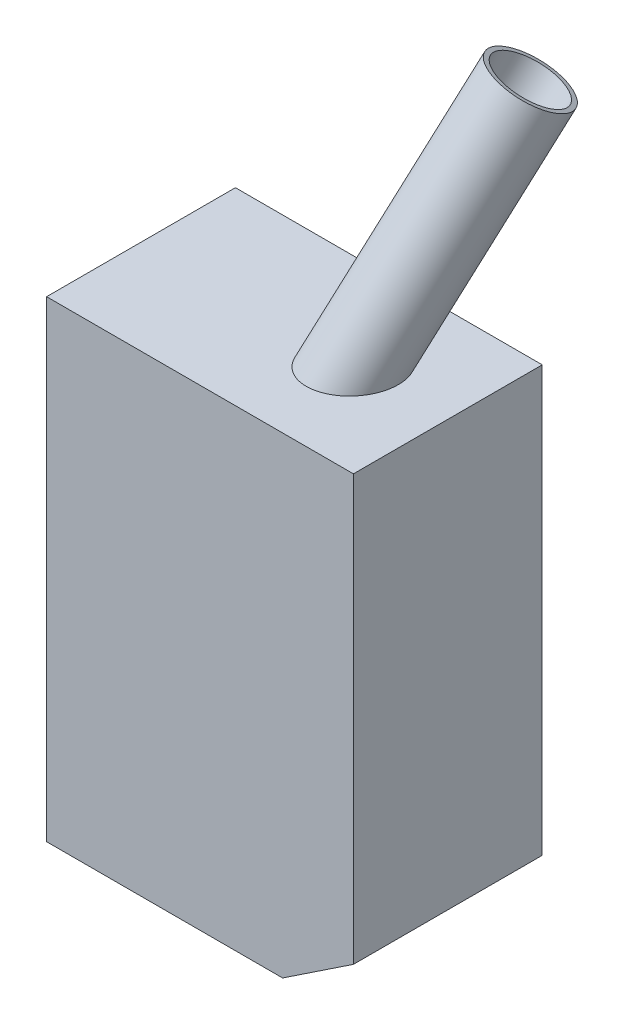
SolidWorks part; units mm, degrees
ref_plane "Front Plane" through (0, 0, 0) normal (0, 0, 1) x (1, 0, 0)
ref_plane "Top Plane" through (0, 0, 0) normal (0, 1, 0) x (1, 0, 0)
ref_plane "Right Plane" through (0, 0, 0) normal (1, 0, 0) x (0, 0, -1)
sketch "Sketch1" plane through (0, 0, 0) normal (0, 1, 0) x (1, 0, 0)
  line L1 (-82.55, -50.8) -> (82.55, -50.8)
  line L2 (-82.55, -50.8) -> (-82.55, 50.8)
  line L3 (-82.55, 50.8) -> (82.55, 50.8)
  line L4 (82.55, -50.8) -> (82.55, 50.8)
  line L5 (-82.55, -50.8) -> (82.55, 50.8) construction
  line L6 (-82.55, 50.8) -> (82.55, -50.8) construction
  point P0 (0, 0)
  dimension "D1" = 165.1
  dimension "D2" = 101.6
extrude "Boss-Extrude1" add sketch "Sketch1" along normal blind 254
sketch "Sketch2" plane through (0, 0, -50.8) normal (0, 0, -1) x (-1, 0, 0)
  line L0 (-44.45, 0) -> (-82.55, 25.4)
  line L1 (-82.55, 0) -> (82.55, 0) construction
  line L2 (-82.55, 254) -> (-82.55, 0) construction
  line L3 (-82.55, 25.4) -> (-82.55, 0)
  line L4 (-82.55, 0) -> (-44.45, 0)
  dimension "D1" = 25.4
  dimension "D2" = 127
extrude "Cut-Extrude1" cut sketch "Sketch2" against normal blind 254
sketch3d "3DSketch1"
  line L0 (49.8123, 254, 0) -> (104.0644, 254, 0) construction
  line L1 (31.75, 254, 0) -> (31.75, 254, -50000) construction
  line L2 (82.55, 254, 50.8) -> (82.55, 254, -50.8) construction
  line L3 (-82.55, 254, 50.8) -> (82.55, 254, 50.8) construction
  line L4 (31.75, 254, 0) -> (31.75, 50254, 0) construction
  line L5 (31.75, 254, 0) -> (71.194, 386.3694, -64.407)
  point P4 (31.75, 254, 0)
  dimension "D1" = 50.8
  dimension "D2" = 50.8
  dimension "D3" = 75
  dimension "D4" = 65
  dimension "D5" = 152.4
ref_plane "Plane3" through (31.75, 254, 0) normal (0.2588, 0.8686, -0.4226) x (0.9658, -0.24, 0.0983)
sketch "Sketch5" plane through (31.75, 254, 0) normal (0.2588, 0.8686, -0.4226) x (0.9658, -0.24, 0.0983)
  circle A0 centre (0, 0) radius 20.447
  dimension "D1" = 40.894
extrude "Boss-Extrude3" add sketch "Sketch5" along normal blind 139.7 and the other way up to surface other way up to face at (0, 254, 0)
shell "Shell2" thickness 2.54
